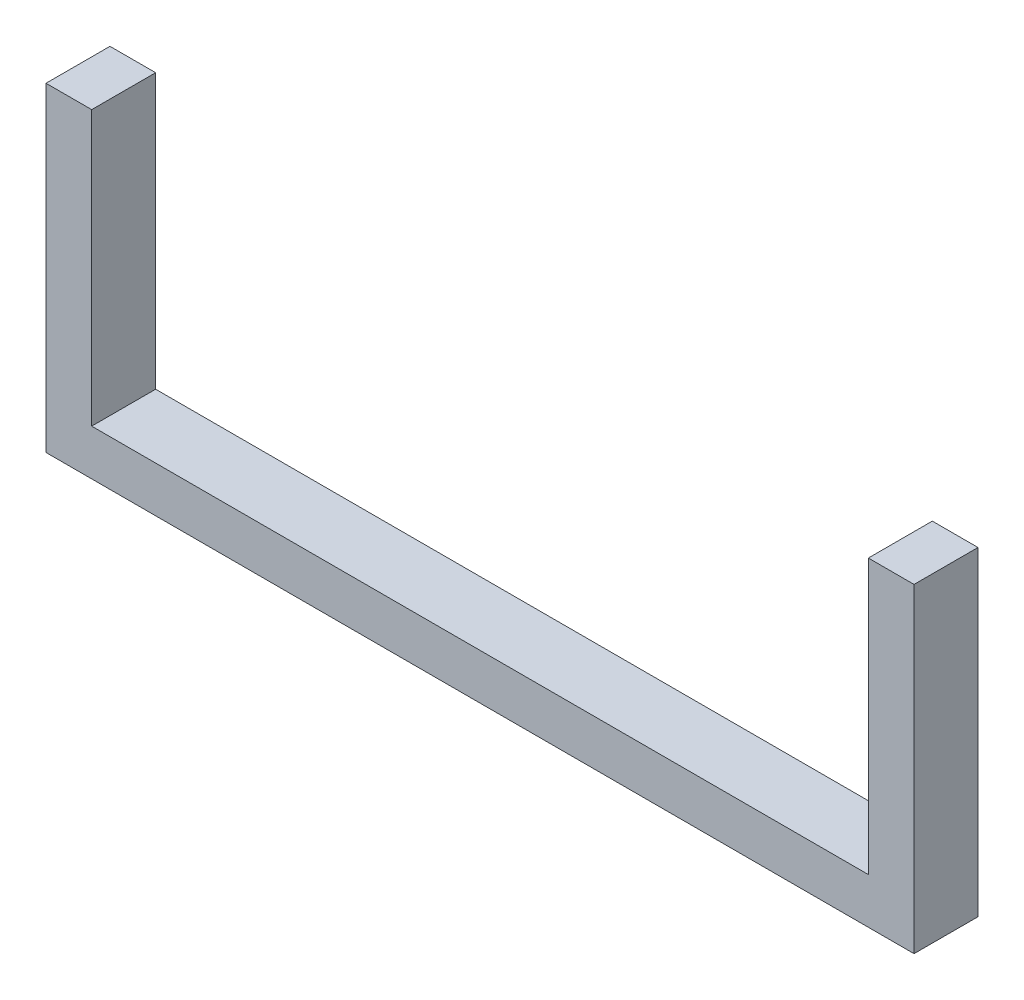
SolidWorks part; units mm, degrees
ref_plane "Front Plane" through (0, 0, 0) normal (0, 0, 1) x (1, 0, 0)
ref_plane "Top Plane" through (0, 0, 0) normal (0, 1, 0) x (1, 0, 0)
ref_plane "Right Plane" through (0, 0, 0) normal (1, 0, 0) x (0, 0, -1)
sketch "Sketch1" plane through (0, 0, 0) normal (0, 1, 0) x (1, 0, 0)
  line L1 (0, 0) -> (190, 0)
  line L2 (0, 0) -> (0, 14)
  line L3 (0, 14) -> (190, 14)
  line L4 (190, 0) -> (190, 14)
  dimension "D1" = 14
  dimension "D2" = 190
extrude "Boss-Extrude1" add sketch "Sketch1" along normal blind 10
sketch "Sketch2" plane through (0, 10, 0) normal (0, 1, 0) x (1, 0, 0)
  line L0 (0, 0) -> (190, 0) construction
  line L1 (0, 14) -> (10, 14)
  line L2 (0, 14) -> (0, 0)
  line L3 (0, 0) -> (10, 0)
  line L4 (10, 14) -> (10, 0)
  line L5 (190, 14) -> (0, 14) construction
  line L6 (190, 0) -> (180, 0)
  line L7 (190, 0) -> (190, 14)
  line L8 (190, 14) -> (180, 14)
  line L9 (180, 0) -> (180, 14)
  dimension "D1" = 10
  dimension "D2" = 10
extrude "Boss-Extrude2" add sketch "Sketch2" along normal blind 60
